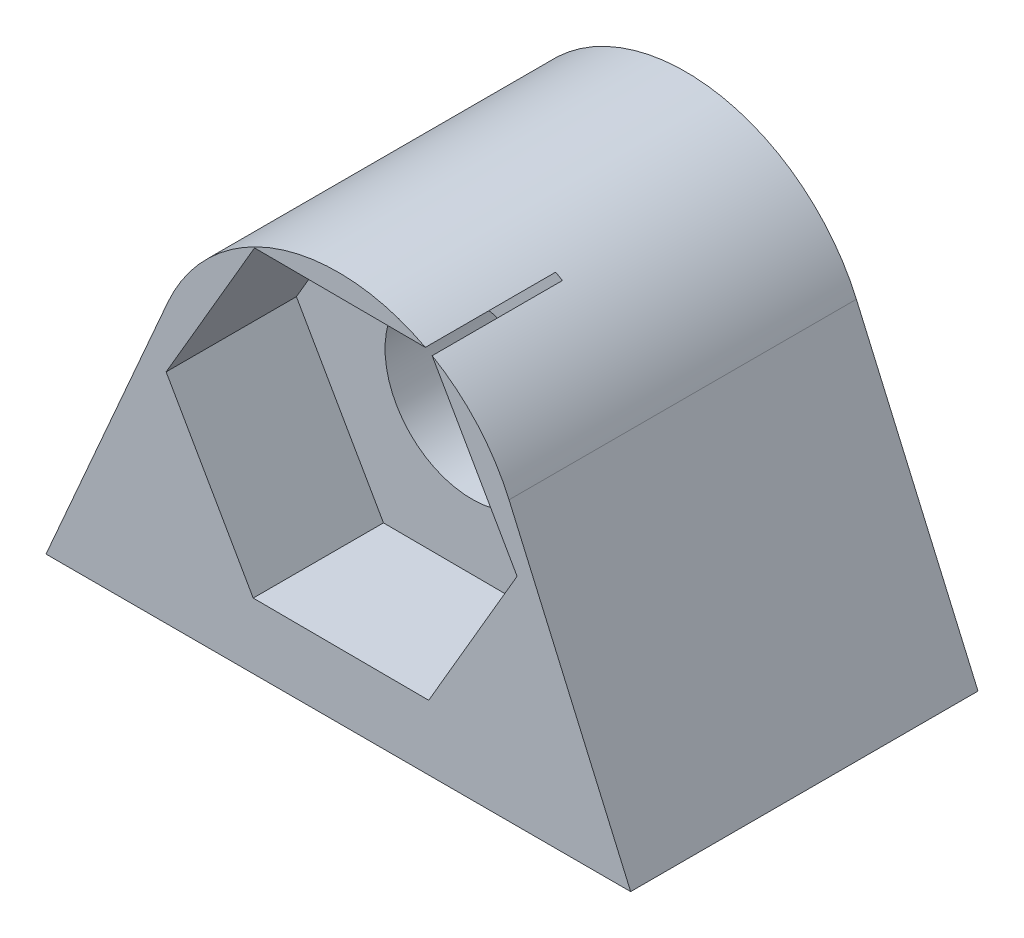
SolidWorks part; units mm, degrees
ref_plane "Alzado" through (0, 0, 0) normal (0, 0, 1) x (1, 0, 0)
ref_plane "Planta" through (0, 0, 0) normal (0, 1, 0) x (1, 0, 0)
ref_plane "Vista lateral" through (0, 0, 0) normal (1, 0, 0) x (0, 0, -1)
sketch "Croquis1" plane through (0, 0, 0) normal (0, 0, 1) x (1, 0, 0)
  line L0 (0, 0) -> (-6.7329, 0)
  line L1 (-6.7329, 0) -> (-3.9317, 6.4151)
  line L2 (3.9317, 6.4151) -> (6.7329, 0)
  line L3 (6.7329, 0) -> (0, 0)
  arc A0 (-3.9317, 6.4151) -> (3.9317, 6.4151) centre (0, 4.6983) cw
  circle A1 centre (0.0757, 5) radius 2
  point P9 (-6.7329, 0)
  dimension "D1" = 4
  dimension "D2" = 5
  dimension "D3" = 7
extrude "Saliente-Extruir1" add sketch "Croquis1" along normal blind 8
sketch "Croquis2" plane through (0, 0, 8) normal (0, 0, 1) x (1, 0, 0)
  line L1 (-1.9603, 1.5089) -> (2.0812, 1.4912)
  line L2 (2.0812, 1.4912) -> (4.1172, 4.9823)
  line L3 (4.1172, 4.9823) -> (2.1117, 8.4911)
  line L4 (2.1117, 8.4911) -> (-1.9297, 8.5088)
  line L5 (-1.9297, 8.5088) -> (-3.9657, 5.0177)
  line L6 (-3.9657, 5.0177) -> (-1.9603, 1.5089)
  circle A0 centre (0.0757, 5) radius 3.5 construction
  point P1 (2.1117, 1.5089)
  dimension "D1" = 7
extrude "Cortar-Extruir1" cut sketch "Croquis2" against normal blind 3
